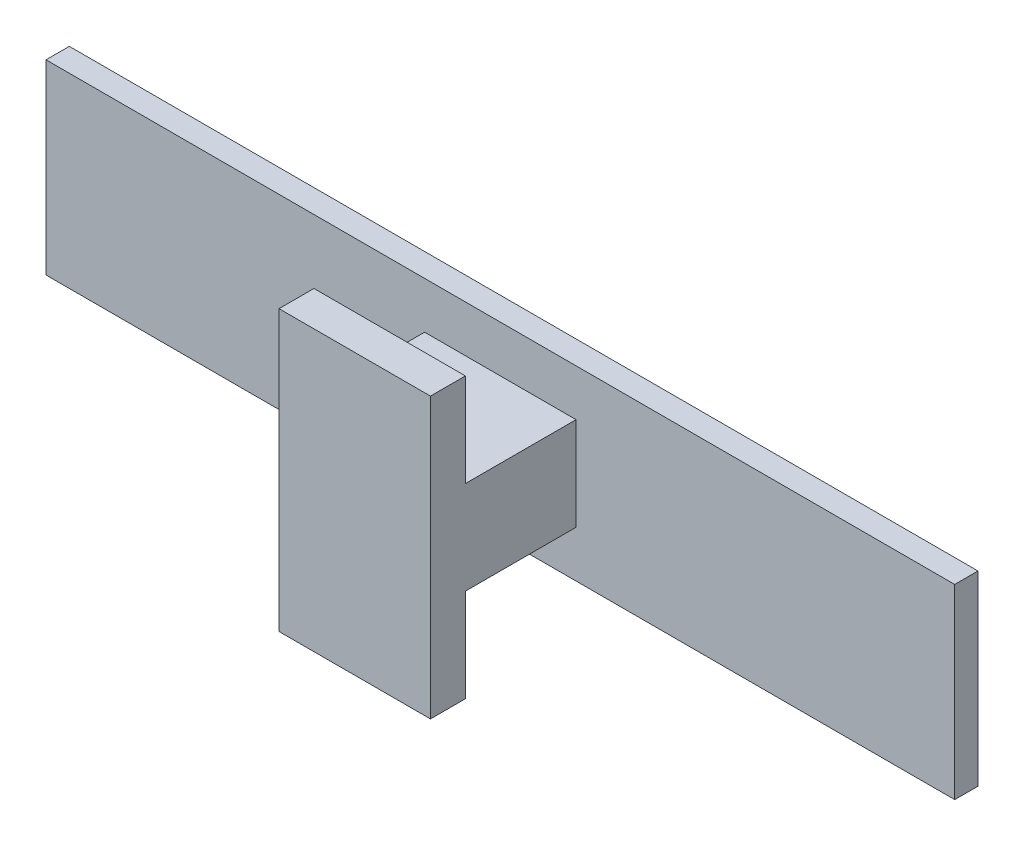
SolidWorks part; units mm, degrees
ref_plane "Front Plane" through (0, 0, 0) normal (0, 0, 1) x (1, 0, 0)
ref_plane "Top Plane" through (0, 0, 0) normal (0, 1, 0) x (1, 0, 0)
ref_plane "Right Plane" through (0, 0, 0) normal (1, 0, 0) x (0, 0, -1)
sketch "Sketch1" plane through (0, 0, 0) normal (0, 0, 1) x (1, 0, 0)
  line L1 (39, -8) -> (-39, -8)
  line L2 (39, -8) -> (39, 8)
  line L3 (39, 8) -> (-39, 8)
  line L4 (-39, -8) -> (-39, 8)
  line L5 (39, -8) -> (-39, 8) construction
  line L6 (39, 8) -> (-39, -8) construction
  point P0 (0, 0)
  dimension "D1" = 78
  dimension "D2" = 16
extrude "Boss-Extrude1" add sketch "Sketch1" along normal blind 2
sketch "Sketch2" plane through (0, 0, 2) normal (0, 0, 1) x (1, 0, 0)
  line L1 (6.5, -4) -> (-6.5, -4)
  line L2 (6.5, -4) -> (6.5, 4)
  line L3 (6.5, 4) -> (-6.5, 4)
  line L4 (-6.5, -4) -> (-6.5, 4)
  line L5 (6.5, -4) -> (-6.5, 4) construction
  line L6 (6.5, 4) -> (-6.5, -4) construction
  point P0 (0, 0)
  dimension "D1" = 8
  dimension "D2" = 13
extrude "Boss-Extrude2" add sketch "Sketch2" along normal blind 9.5
sketch "Sketch3" plane through (0, 0, 11.5) normal (0, 0, 1) x (1, 0, 0)
  line L1 (6.5, -12) -> (-6.5, -12)
  line L2 (6.5, -12) -> (6.5, 12)
  line L3 (6.5, 12) -> (-6.5, 12)
  line L4 (-6.5, -12) -> (-6.5, 12)
  line L5 (6.5, -12) -> (-6.5, 12) construction
  line L6 (6.5, 12) -> (-6.5, -12) construction
  point P0 (0, 0)
  dimension "D1" = 13
  dimension "D2" = 24
extrude "Boss-Extrude3" add sketch "Sketch3" along normal blind 3
